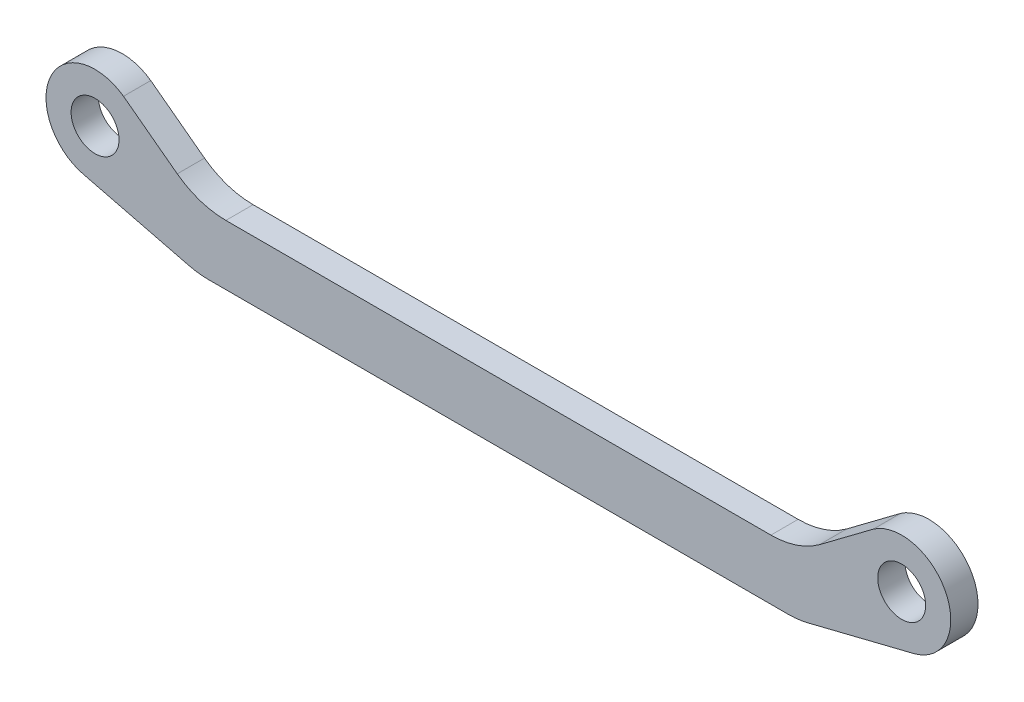
SolidWorks part; units mm, degrees
ref_plane "Plan de face" through (0, 0, 0) normal (0, 0, 1) x (1, 0, 0)
ref_plane "Plan de dessus" through (0, 0, 0) normal (0, 1, 0) x (1, 0, 0)
ref_plane "Plan de droite" through (0, 0, 0) normal (1, 0, 0) x (0, 0, -1)
sketch "Esquisse1" plane through (0, 0, 0) normal (0, 0, 1) x (1, 0, 0)
  line L0 (-75.5919, -6.0967) -> (-56.3989, -10.8728)
  line L1 (-52.7767, -11.3167) -> (53.5484, -11.3167)
  line L2 (57.1706, -10.8728) -> (76.3636, -6.0967)
  line L3 (69.167, 10.0156) -> (59.3056, 2.6235)
  line L4 (50.3858, -0.3167) -> (-49.6142, -0.3167)
  line L5 (-58.534, 2.6235) -> (-68.3953, 10.0156)
  arc A1 (-68.3953, 10.0156) -> (-75.5919, -6.0967) centre (-73.6142, 2.6833) ccw
  arc A2 (76.3636, -6.0967) -> (69.167, 10.0156) centre (74.3858, 2.6833) ccw
  arc A4 (-56.3989, -10.8728) -> (-52.7767, -11.3167) centre (-52.7767, 3.6833) ccw
  arc A5 (53.5484, -11.3167) -> (57.1706, -10.8728) centre (53.5484, 3.6833) ccw
  arc A6 (50.3858, -0.3167) -> (59.3056, 2.6235) centre (50.3858, 14.6833) ccw
  arc A7 (-58.534, 2.6235) -> (-49.6142, -0.3167) centre (-49.6142, 14.6833) ccw
  circle A8 centre (-73.6142, 2.6833) radius 4.4
  circle A9 centre (74.3858, 2.6833) radius 4.4
  dimension "D1" = 15
  dimension "D2" = 15
  dimension "D3" = 8.8
  dimension "D4" = 8.8
  dimension "D5" = 9
  dimension "D6" = 9
extrude "Boss.-Extru.1" add sketch "Esquisse1" along normal blind 5
